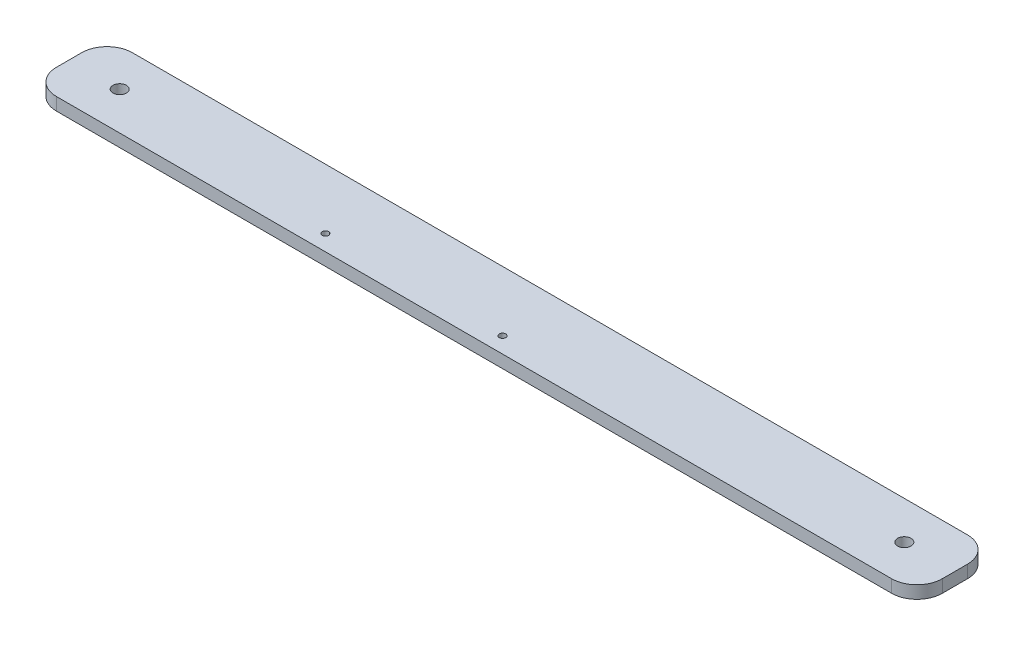
SolidWorks part; units mm, degrees
ref_plane "Front Plane" through (0, 0, 0) normal (0, 0, 1) x (1, 0, 0)
ref_plane "Top Plane" through (0, 0, 0) normal (0, 1, 0) x (1, 0, 0)
ref_plane "Right Plane" through (0, 0, 0) normal (1, 0, 0) x (0, 0, -1)
sketch "Sketch1" plane through (0, 0, 0) normal (0, 1, 0) x (1, 0, 0)
  line L1 (0, 0) -> (444.5, 0)
  line L2 (0, 0) -> (0, 38.1)
  line L3 (0, 38.1) -> (444.5, 38.1)
  line L4 (444.5, 0) -> (444.5, 38.1)
  dimension "D1" = 444.5
  dimension "D2" = 38.1
extrude "Boss-Extrude1" add sketch "Sketch1" along normal blind 6.35
fillet "Fillet1" radius 12.7 1 edges at (0, 3.175, 0)
fillet "Fillet2" radius 12.7 1 edges at (0, 3.175, -38.1)
fillet "Fillet3" radius 12.7 1 edges at (444.5, 3.175, -38.1)
fillet "Fillet4" radius 12.7 1 edges at (444.5, 3.175, 0)
sketch "Sketch2" plane through (0, 6.35, 0) normal (0, 1, 0) x (1, 0, 0)
  line L0 (431.8, 38.1) -> (12.7, 38.1) construction
  line L1 (0, 25.4) -> (0, 12.7) construction
  circle A0 centre (25.4, 19.05) radius 3.3782
  dimension "D1" = 19.05
  dimension "D2" = 25.4
extrude "Cut-Extrude1" cut sketch "Sketch2" against normal through all
sketch "Sketch4" plane through (0, 6.35, 0) normal (0, 1, 0) x (1, 0, 0)
  line L0 (431.8, 38.1) -> (12.7, 38.1) construction
  line L1 (444.5, 12.7) -> (444.5, 25.4) construction
  circle A0 centre (419.1, 19.05) radius 3.3782
  dimension "D1" = 19.05
  dimension "D2" = 25.4
extrude "Cut-Extrude2" cut sketch "Sketch4" against normal through all
hole_wizard "CSK for #4 Flat Head Machine Screw1" positions "Sketch6" profile "Sketch5" countersink size "#4" standard "ANSI Inch" end condition through all
sketch "Sketch6" plane through (0, 0, 0) normal (0, -1, 0) x (-1, 0, 0)
  line L0 (-12.7, 0) -> (-431.8, 0) construction
  circle A0 centre (-139.7, 7.9375) radius 1.1303 construction
  circle A1 centre (-228.6, 7.9375) radius 1.1303 construction
  point P0 (-228.6, 7.9375)
  point P2 (-139.7, 7.9375)
  dimension "D1" = 7.9375
  dimension "D2" = 7.9375
  dimension "D3" = 0
  dimension "D4" = 0
sketch "Sketch5" plane through (228.6, 0, -7.9375) normal (1, 0, 0) x (0, 0, -1)
  line L0 (0, 0) -> (0, 6.35)
  line L1 (0, 6.35) -> (1.6319, 6.35)
  line L2 (1.6319, 6.35) -> (1.6319, 1.4098)
  line L3 (1.6319, 1.4098) -> (2.8575, 0)
  line L5 (2.8575, 0) -> (0, 0)
  line L6 (-1.6319, 1.4098) -> (-2.8575, 0) construction
  line L11 (0, -6.35) -> (0, 107.95) construction
  dimension "Thru Hole Dia." = 3.2639
  dimension "Thru Hole Depth" = 6.35
  dimension "Near C'Sink Dia." = 5.715
  dimension "Near C'Sink Angle" = 82
